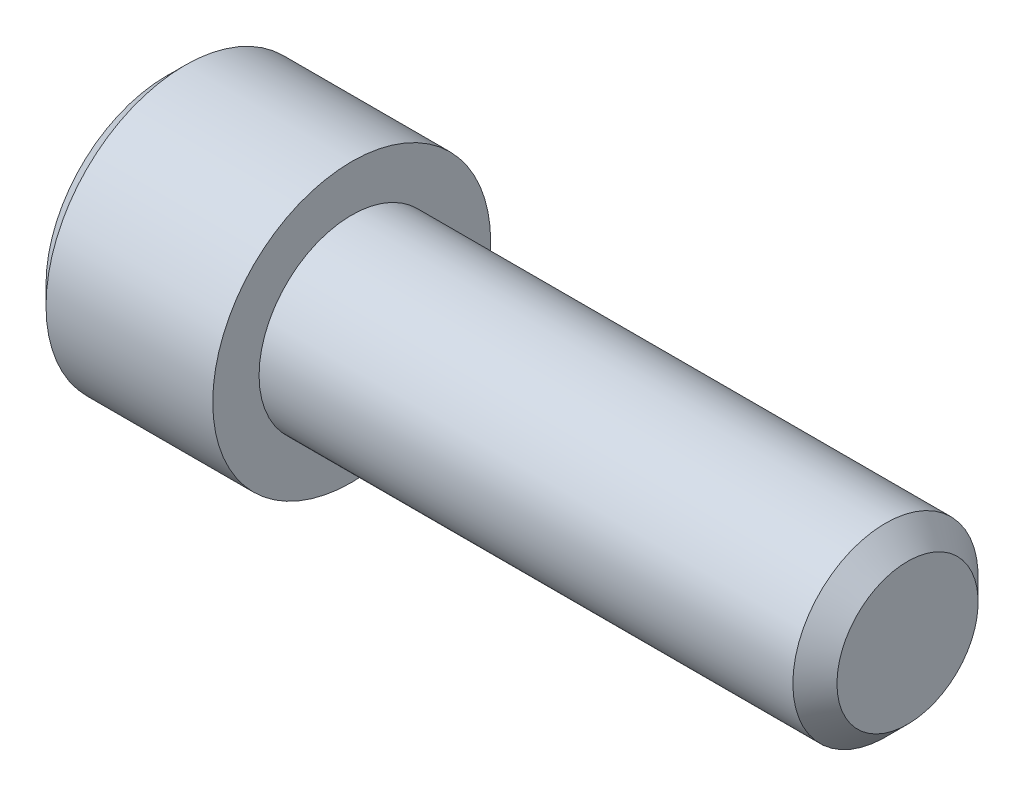
SolidWorks part; units mm, degrees
revolve "Base-Revolve" add sketch "BodySke"
sketch "BodySke" plane through (0, 0, 0) normal (0, 0, 1) x (1, 0, 0)
  line L0 (0, 0) -> (0, 4.1275)
  line L1 (0.635, 4.7625) -> (6.35, 4.7625)
  line L2 (6.35, 4.7625) -> (6.35, 3.175)
  line L3 (6.35, 3.175) -> (24.6443, 3.175)
  line L4 (25.4, 2.4193) -> (25.4, 0)
  line L5 (25.4, 0) -> (0, 0)
  line L6 (-31.75, 0) -> (127, 0) construction
  line L7 (0, 4.1275) -> (0.635, 4.7625)
  line L8 (25.4, 2.4193) -> (24.6443, 3.175)
  line L9 (0, -4.1275) -> (0.635, -4.7625) construction
  line L10 (25.4, -2.4193) -> (24.6443, -3.175) construction
  line L11 (7.62, 9.525) -> (7.62, 3.175) construction
  line L12 (6.35, 9.525) -> (6.35, 3.175) construction
  line L13 (-12.7, 9.525) -> (-12.7, 3.175) construction
  dimension "Diameter" = 6.35
  dimension "Head_ht" = 6.35
  dimension "Length" = 19.05
  dimension "Body_ch_ang" = 45
  dimension "Head_dia" = 9.525
  dimension "Head_ch_ang" = 45
  dimension "Head_side_ht" = 5.715
  dimension "Minor_dia" = 4.8387
  dimension "Advance" = 1.27
  dimension "Thread_nom" = 19.05
  dimension "Thread_length" = 38.1
cosmetic thread "ThreadCosmetic" [suppressed]
fillet "Fillet1" [suppressed] radius 0.3556
material "Plain Carbon Steel"
ref_plane "Plane1" through (0, 0, 0) normal (0, 0, 1) x (1, 0, 0)
ref_plane "Plane2" through (0, 0, 0) normal (0, 1, 0) x (1, 0, 0)
ref_plane "Plane3" through (0, 0, 0) normal (1, 0, 0) x (0, 0, -1)
sketch "Sketch2" plane through (0, 0, 0) normal (0, 0, 1) x (1, 0, 0)
  line L0 (0, 2.3812) -> (3.048, 2.3813)
  line L1 (3.048, 2.3813) -> (4.4228, 0)
  line L2 (-31.75, 0) -> (127, 0) construction
  line L3 (4.4228, 0) -> (0, 0)
  line L4 (0, 0) -> (0, 2.3812)
  line L5 (0, 4.1275) -> (0, -4.1275) construction
  line L6 (0, 0) -> (47.625, 0) construction
  line L7 (6.35, -4.7625) -> (6.35, 4.7625) construction
  dimension "D1" = 2.3813
  dimension "D2" = 60
revolve "Hex-PreBroach" [suppressed] cut sketch "Sketch2" angle 360 about L6
sketch "Sketch3" plane through (0, 0, 0) normal (-1, 0, 0) x (0, 0.5, 0.866)
  line L0 (1.3748, 2.3813) -> (-1.3748, 2.3813)
  line L1 (-1.3748, 2.3813) -> (-2.7496, 0)
  line L2 (1.3748, 2.3813) -> (2.7496, 0)
  line L3 (1.3748, -2.3812) -> (2.7496, 0)
  line L4 (1.3748, -2.3812) -> (-1.3748, -2.3812)
  line L5 (-1.3748, -2.3812) -> (-2.7496, 0)
  dimension "D1" = 2.3813
  dimension "D2" = 2.3813
  dimension "Hex_size" = 4.7625
extrude "Hex" cut sketch "Sketch3" against normal blind 3.048
sketch "ThdSchSke" plane through (0, 0, 0) normal (0, 0, 1) x (1, 0, 0)
  line L0 (7.62, -2.4193) -> (7.0909, -3.175)
  line L1 (7.62, -2.4193) -> (8.1491, -3.175)
  line L2 (8.1491, -3.175) -> (8.1491, -3.9688)
  line L3 (-3.175, 0) -> (5.1513, 0) construction
  line L5 (8.1491, -3.9688) -> (7.0909, -3.9688)
  line L6 (7.0909, -3.9688) -> (7.0909, -3.175)
  line L7 (0, 4.1275) -> (0, -4.1275) construction
  dimension "Thread_minor" = 4.8387
  dimension "Diameter" = 6.35
  dimension "Start" = 7.62
revolve "ThreadSchematic" [suppressed] cut sketch "ThdSchSke" angle 360 about L3
other "Freeze***"
equation "\"D2@Sketch3\" = \"Hex_size@Sketch3\" / 2"
equation "\"D1@Sketch3\" = \"Hex_size@Sketch3\" / 2"
equation "\"D1@Sketch2\" = \"Hex_size@Sketch3\" / 2"
equation "\"Thread_minor@ThreadCosmetic\" = \"Minor_dia@BodySke\""
equation "\"Wall_thickness@Sketch2\" = \"Head_ht@BodySke\" - \"Key_eng@Hex\""
equation "\"Thread_length@ThreadCosmetic\" =  (  ( sgn (  ( \"Length@BodySke\" - \"Advance@BodySke\" )  - \"Thread_nom@BodySke\" )  - 1 )  *  (  ( \"Length@BodySke\" - \"Advance@BodySke\" )  - \"Thread_nom@BodySke\" )  )  /  - 2 + \"Thread_nom@BodySke\""
equation "\"Thread_minor@ThdSchSke\" = \"Minor_dia@BodySke\""
equation "\"Diameter@ThdSchSke\" = \"Diameter@BodySke\""
equation "\"Overcut@ThdSchSke\" = \"Diameter@BodySke\" * 1.25"
equation "\"Start@ThdSchSke\" = \"Head_ht@BodySke\" + \"Length@BodySke\" - \"Thread_length@ThreadCosmetic\"'---Non-countersunk---"
